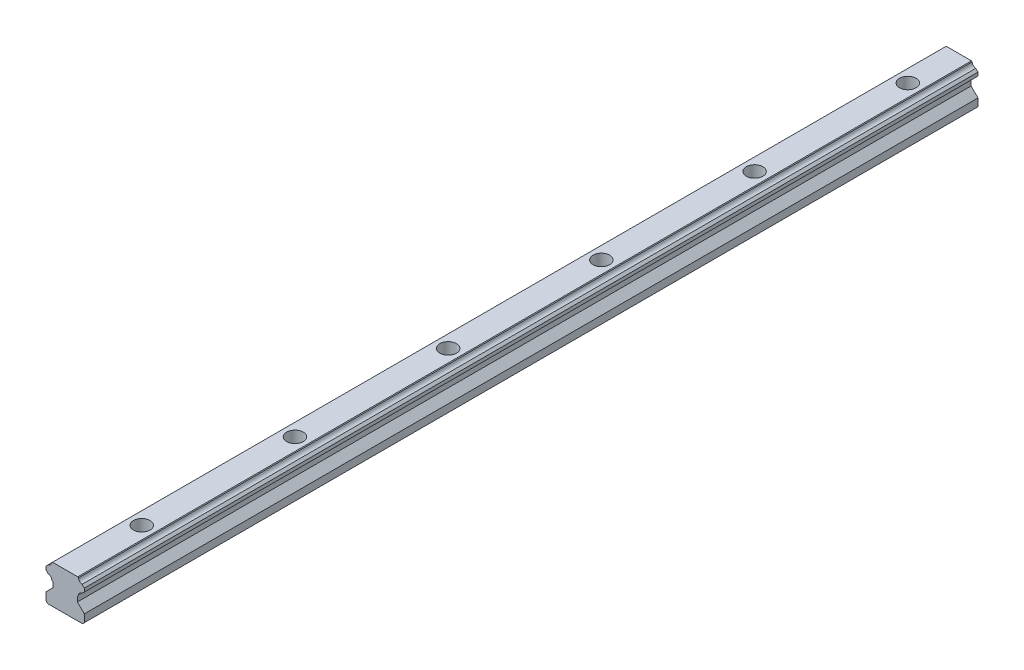
SolidWorks part; units mm, degrees
ref_plane "Спереди" through (0, 0, 0) normal (0, 0, 1) x (1, 0, 0)
ref_plane "Сверху" through (0, 0, 0) normal (0, 1, 0) x (1, 0, 0)
ref_plane "Справа" through (0, 0, 0) normal (1, 0, 0) x (0, 0, -1)
sketch "Model" plane through (0, 0, 0) normal (0, 0, 1) x (1, 0, 0)
  line L7 (6.8, 0) -> (7.5, 0.7)
  line L8 (7.5, 0.7) -> (7.5, 3.6994)
  line L9 (7.5, 3.6994) -> (4.7998, 6.3996)
  line L10 (4.7998, 6.3996) -> (4.7998, 8.4091)
  line L11 (4.7998, 8.4091) -> (5.2008, 8.8101)
  line L12 (6.6481, 10.2574) -> (7.5, 11.1093)
  line L13 (7.5, 11.1093) -> (7.5, 12.4495)
  line L14 (7.5, 12.4495) -> (6.6345, 13.315)
  line L15 (5.2023, 14.7472) -> (4.9495, 15)
  line L16 (4.9495, 15) -> (-4.9495, 15)
  line L17 (-4.9495, 15) -> (-5.2023, 14.7472)
  line L18 (-6.6345, 13.315) -> (-7.5, 12.4495)
  line L19 (-7.5, 12.4495) -> (-7.5, 11.1093)
  line L20 (-7.5, 11.1093) -> (-6.6481, 10.2574)
  line L21 (-5.2008, 8.8101) -> (-4.7998, 8.4091)
  line L22 (-4.7998, 8.4091) -> (-4.7998, 6.3996)
  line L23 (-4.7998, 6.3996) -> (-7.5, 3.6994)
  line L24 (-7.5, 3.6994) -> (-7.5, 0.7)
  line L25 (-7.5, 0.7) -> (-6.8, 0)
  line L26 (-6.8, 0) -> (6.8, 0)
  arc A0 (6.6481, 10.2574) -> (5.2008, 8.8101) centre (6.8215, 8.6367) ccw
  arc A1 (5.2023, 14.7472) -> (6.6345, 13.315) centre (6.8215, 14.9342) ccw
  arc A2 (-6.6345, 13.315) -> (-5.2023, 14.7472) centre (-6.8215, 14.9342) ccw
  arc A3 (-5.2008, 8.8101) -> (-6.6481, 10.2574) centre (-6.8215, 8.6367) ccw
extrude "Бобышка-Вытянуть1" add sketch "Model" along normal blind 600
sketch "Эскиз2" plane through (0, 15, 0) normal (0, 1, 0) x (1, 0, 0)
  line L0 (0, 43.9966) -> (0, -648.9514) construction
  line L1 (4.9495, 0) -> (-4.9495, 0) construction
  circle A0 centre (0, -30) radius 3.25
  circle A1 centre (0, -90) radius 3.25
  circle A2 centre (0, -150) radius 3.25
  circle A3 centre (0, -210) radius 3.25
  circle A4 centre (0, -270) radius 3.25
  circle A5 centre (0, -330) radius 3.25
  circle A6 centre (0, -390) radius 3.25
  circle A7 centre (0, -450) radius 3.25
  circle A8 centre (0, -510) radius 3.25
  circle A9 centre (0, -570) radius 3.25
  dimension "D1" = 10
  dimension "D2" = 30
extrude "Вырез-Вытянуть1" cut sketch "Эскиз2" against normal blind 5.3
sketch "Эскиз3" plane through (0, 9.7, 0) normal (0, 1, 0) x (1, 0, 0)
  circle A0 centre (0, -30) radius 2.25
  circle A1 centre (0, -90) radius 2.25
  circle A2 centre (0, -150) radius 2.25
  circle A3 centre (0, -210) radius 2.25
  circle A4 centre (0, -270) radius 2.25
  circle A5 centre (0, -330) radius 2.25
  circle A6 centre (0, -390) radius 2.25
  circle A7 centre (0, -450) radius 2.25
  circle A8 centre (0, -510) radius 2.25
  circle A9 centre (0, -570) radius 2.25
  dimension "D1" = 10
extrude "Вырез-Вытянуть2" cut sketch "Эскиз3" against normal through all
sketch "Sketch1" plane through (0, 15, 0) normal (0, 1, 0) x (1, 0, 0)
  line L0 (7.5, -600) -> (7.5, 0) construction
  line L1 (-7.5, 0) -> (7.5, 0)
  line L2 (-7.5, 0) -> (-7.5, -250)
  line L3 (-7.5, -250) -> (7.5, -250)
  line L4 (7.5, 0) -> (7.5, -250)
  dimension "D1" = 250
extrude "Cut-Extrude1" cut sketch "Sketch1" against normal blind 100
